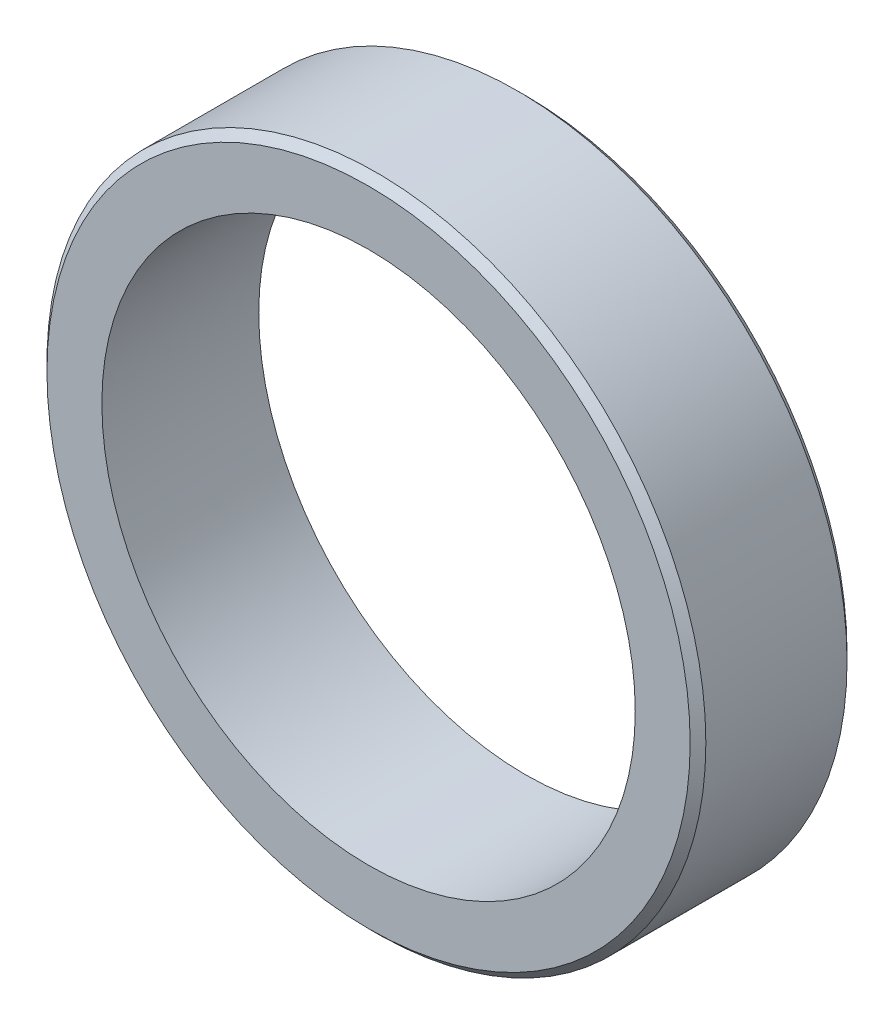
SolidWorks part; units mm, degrees
material "BUTYL"
ref_plane "前视基准面" through (0, 0, 0) normal (0, 0, 1) x (1, 0, 0)
ref_plane "上视基准面" through (0, 0, 0) normal (0, 1, 0) x (1, 0, 0)
ref_plane "右视基准面" through (0, 0, 0) normal (1, 0, 0) x (0, 0, -1)
sketch "草图1" plane through (0, 0, 0) normal (0, 0, 1) x (1, 0, 0)
  circle A0 centre (0, 0) radius 340
  circle A1 centre (0, 0) radius 420
  dimension "D1" = 680
  dimension "D2" = 80
extrude "凸台-拉伸1" add sketch "草图1" along normal mid plane 200
chamfer "倒角1" distance 10 angle 45 2 edges at (420, 0, -100) (420, 0, 100)
